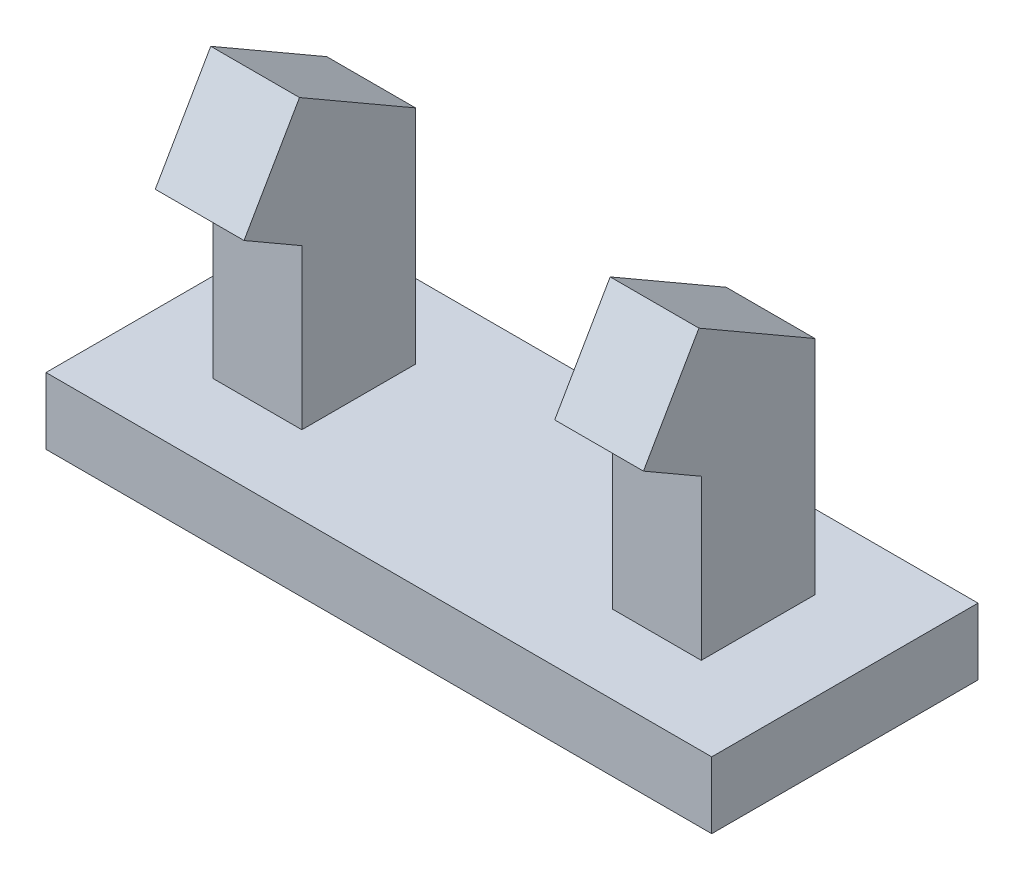
SolidWorks part; units mm, degrees
ref_plane "Front Plane" through (0, 0, 0) normal (0, 0, 1) x (1, 0, 0)
ref_plane "Top Plane" through (0, 0, 0) normal (0, 1, 0) x (1, 0, 0)
ref_plane "Right Plane" through (0, 0, 0) normal (1, 0, 0) x (0, 0, -1)
sketch "Sketch1" plane through (0, 0, 0) normal (1, 0, 0) x (0, 0, -1)
  line L4 (0, 0) -> (60, 0)
  line L5 (60, 0) -> (60, 15)
  line L6 (60, 15) -> (43.2667, 15)
  line L7 (0, 15) -> (0, 0)
  line L21 (17.6501, 15) -> (0, 15)
  line L23 (17.6501, 15) -> (17.6501, 50.9222)
  line L24 (17.6501, 50.9222) -> (4.6217, 58.4442)
  line L25 (4.6217, 58.4442) -> (17.1217, 80.0948)
  line L26 (17.1217, 80.0948) -> (43.2667, 65)
  line L27 (43.2667, 65) -> (43.2667, 15)
extrude "Boss-Extrude1" add sketch "Sketch1" along normal blind 75
sketch "Sketch6" plane through (0, 0, 0) normal (-1, 0, 0) x (0, 0, 1)
  line L0 (-43.2667, 15) -> (-17.6501, 15)
  line L1 (-17.6501, 15) -> (-17.6501, 50.9222)
  line L2 (-17.6501, 50.9222) -> (-4.6217, 58.4442)
  line L3 (-4.6217, 58.4442) -> (-17.1217, 80.0948)
  line L4 (-17.1217, 80.0948) -> (-43.2667, 65)
  line L5 (-43.2667, 65) -> (-43.2667, 15)
extrude "Cut-Extrude5" cut sketch "Sketch6" against normal blind 20
sketch "Sketch7" plane through (75, 0, 0) normal (1, 0, 0) x (0, 0, -1)
  line L0 (17.6501, 15) -> (43.2667, 15)
  line L1 (43.2667, 15) -> (43.2667, 65)
  line L2 (43.2667, 65) -> (17.1217, 80.0948)
  line L3 (17.1217, 80.0948) -> (4.6217, 58.4442)
  line L4 (4.6217, 58.4442) -> (17.6501, 50.9222)
  line L5 (17.6501, 50.9222) -> (17.6501, 15)
extrude "Cut-Extrude6" cut sketch "Sketch7" against normal blind 35
mirror "Mirror2" about plane through (75, 0, 0) normal (1, 0, 0) of "Boss-Extrude1", "Cut-Extrude5", "Cut-Extrude6"
